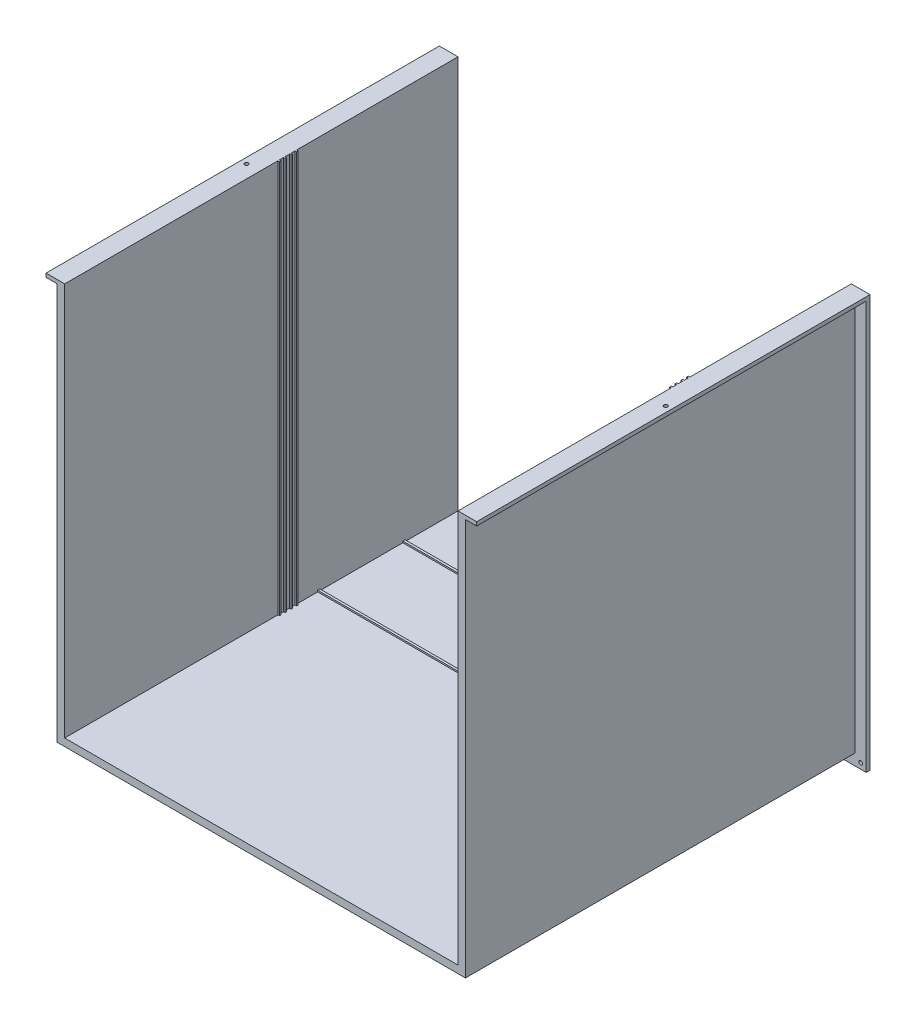
SolidWorks part; units mm, degrees
ref_plane "Front Plane" through (0, 0, 0) normal (0, 0, 1) x (1, 0, 0)
ref_plane "Top Plane" through (0, 0, 0) normal (0, 1, 0) x (1, 0, 0)
ref_plane "Right Plane" through (0, 0, 0) normal (1, 0, 0) x (0, 0, -1)
sketch "Sketch1" plane through (0, 0, 0) normal (0, 0, 1) x (1, 0, 0)
  line L1 (-263.3488, -263.3488) -> (263.3488, -263.3488)
  line L2 (-263.3488, -263.3488) -> (-263.3488, 263.3488)
  line L4 (263.3488, -263.3488) -> (263.3488, 263.3488)
  line L5 (-263.3488, -263.3488) -> (263.3488, 263.3488) construction
  line L6 (-263.3488, 263.3488) -> (263.3488, -263.3488) construction
  line L7 (273.3488, -273.3488) -> (273.3488, 263.3488)
  line L8 (-273.3488, -273.3488) -> (273.3488, -273.3488)
  line L9 (-273.3488, -273.3488) -> (-273.3488, 263.3488)
  line L10 (-263.3488, 263.3488) -> (-273.3488, 263.3488)
  line L11 (263.3488, 263.3488) -> (273.3488, 263.3488)
  line L12 (273.3488, -273.3488) -> (273.3488, 273.3488) construction
  line L13 (-273.3488, 273.3488) -> (273.3488, 273.3488) construction
  line L14 (-263.3488, 263.3488) -> (263.3488, 263.3488) construction
  line L15 (-273.3488, -273.3488) -> (-273.3488, 273.3488) construction
  point P0 (0, 0)
  dimension "D1" = 10
extrude "Boss-Extrude1" add sketch "Sketch1" along normal blind 526.6976
sketch "Sketch2" plane through (0, -263.3488, 0) normal (0, 1, 0) x (1, 0, 0)
  line L0 (-263.3488, -70.9019) -> (263.3488, -70.9019)
  line L1 (-263.3488, -526.6976) -> (-263.3488, 0) construction
  line L2 (263.3488, -526.6976) -> (263.3488, 0) construction
  line L3 (263.3488, -70.9019) -> (263.3488, -73.9019)
  line L4 (263.3488, -73.9019) -> (-263.3488, -73.9019)
  line L5 (-263.3488, -526.6976) -> (-263.3488, 0) construction
  line L6 (-263.3488, -73.9019) -> (-263.3488, -70.9019)
  line L7 (157.83, -73.9019) -> (157.83, -184.9019) construction
  line L8 (157.83, -129.4019) -> (119.5076, -129.4019) construction
  line L9 (-263.3488, -184.9019) -> (-263.3488, -187.9019)
  line L10 (263.3488, -187.9019) -> (263.3488, -184.9019)
  line L11 (-263.3488, -187.9019) -> (263.3488, -187.9019)
  line L12 (263.3488, -184.9019) -> (-263.3488, -184.9019)
extrude "Boss-Extrude2" add sketch "Sketch2" along normal blind 2
sketch "Sketch3" plane through (0, -263.3488, 0) normal (0, 1, 0) x (1, 0, 0)
  line L0 (-263.3488, -216.2016) -> (-261.1488, -216.2016)
  line L3 (-263.3488, -526.6976) -> (-263.3488, -187.9019) construction
  line L4 (-261.1488, -216.2016) -> (-261.1488, -218.2016)
  line L5 (-261.1488, -218.2016) -> (-263.3488, -218.2016)
  line L6 (-263.3488, -526.6976) -> (-263.3488, 0) construction
  line L7 (-261.1488, -218.2016) -> (-261.1488, -223.7016) construction
  line L8 (-261.1488, -220.9516) -> (-263.3488, -220.9516) construction
  line L9 (-261.1488, -225.7016) -> (-261.1488, -223.7016)
  line L10 (-261.1488, -223.7016) -> (-263.3488, -223.7016)
  line L11 (-263.3488, -225.7016) -> (-261.1488, -225.7016)
  line L12 (0, -187.9019) -> (0, -216.2016) construction
  line L13 (-263.3488, -187.9019) -> (263.3488, -187.9019) construction
  line L14 (-263.3488, -216.2016) -> (-263.3488, -218.2016)
  line L15 (-263.3488, -223.7016) -> (-263.3488, -225.7016)
  line L16 (263.3488, -225.7016) -> (261.1488, -225.7016)
  line L17 (261.1488, -223.7016) -> (263.3488, -223.7016)
  line L18 (261.1488, -225.7016) -> (261.1488, -223.7016)
  line L19 (261.1488, -216.2016) -> (261.1488, -218.2016)
  line L20 (263.3488, -216.2016) -> (263.3488, -218.2016)
  line L21 (261.1488, -218.2016) -> (263.3488, -218.2016)
  line L22 (263.3488, -216.2016) -> (261.1488, -216.2016)
  line L23 (263.3488, -223.7016) -> (263.3488, -225.7016)
extrude "Boss-Extrude3" add sketch "Sketch3" along normal up to surface (526.6976 mm away) up to face at (-268.3488, 263.3488, 263.3488)
ref_plane "Plane1" through (0, 0, 228.7016) normal (0, 0, 1) x (1, 0, 0)
mirror "Mirror1" about plane through (0, 0, 228.7016) normal (0, 0, 1) of "Boss-Extrude3"
sketch "Sketch4" plane through (0, 0, 0) normal (0, 0, -1) x (-1, 0, 0)
  line L0 (-263.3488, 263.3488) -> (-263.3488, -263.3488)
  line L1 (-263.3488, -263.3488) -> (263.3488, -263.3488)
  line L2 (263.3488, -263.3488) -> (263.3488, 263.3488)
  line L3 (-288.3488, 263.3488) -> (-288.3488, -288.3488)
  line L4 (-288.3488, -288.3488) -> (288.3488, -288.3488)
  line L5 (288.3488, -288.3488) -> (288.3488, 263.3488)
  line L6 (-263.3488, 263.3488) -> (-288.3488, 263.3488)
  line L7 (263.3488, 263.3488) -> (288.3488, 263.3488)
  line L8 (-273.3488, -273.3488) -> (-288.3488, -288.3488) construction
  line L9 (273.3488, -273.3488) -> (288.3488, -288.3488) construction
  circle A0 centre (-280.8488, -280.8488) radius 2.5
  circle A1 centre (280.8488, -280.8488) radius 2.5
  dimension "D1" = 25
extrude "Boss-Extrude4" add sketch "Sketch4" against normal blind 5
sketch "Sketch5" plane through (0, 263.3488, 0) normal (0, 1, 0) x (1, 0, 0)
  line L0 (-288.3488, -5) -> (-288.3488, -526.6976)
  line L1 (-288.3488, -526.6976) -> (-273.3488, -526.6976)
  line L2 (-273.3488, -526.6976) -> (-273.3488, -5)
  line L3 (-273.3488, -5) -> (-288.3488, -5)
  line L4 (288.3488, -5) -> (288.3488, -526.6976)
  line L5 (288.3488, -526.6976) -> (273.3488, -526.6976)
  line L6 (273.3488, -526.6976) -> (273.3488, -5)
  line L7 (273.3488, -526.6976) -> (273.3488, -5) construction
  line L8 (273.3488, -5) -> (288.3488, -5) construction
  line L9 (273.3488, -5) -> (288.3488, -5)
  line L10 (0, 0) -> (0, -41.358) construction
  circle A0 centre (-280.7046, -265.8488) radius 2.5
  circle A1 centre (280.7046, -265.8488) radius 2.5
extrude "Boss-Extrude5" add sketch "Sketch5" against normal blind 5
